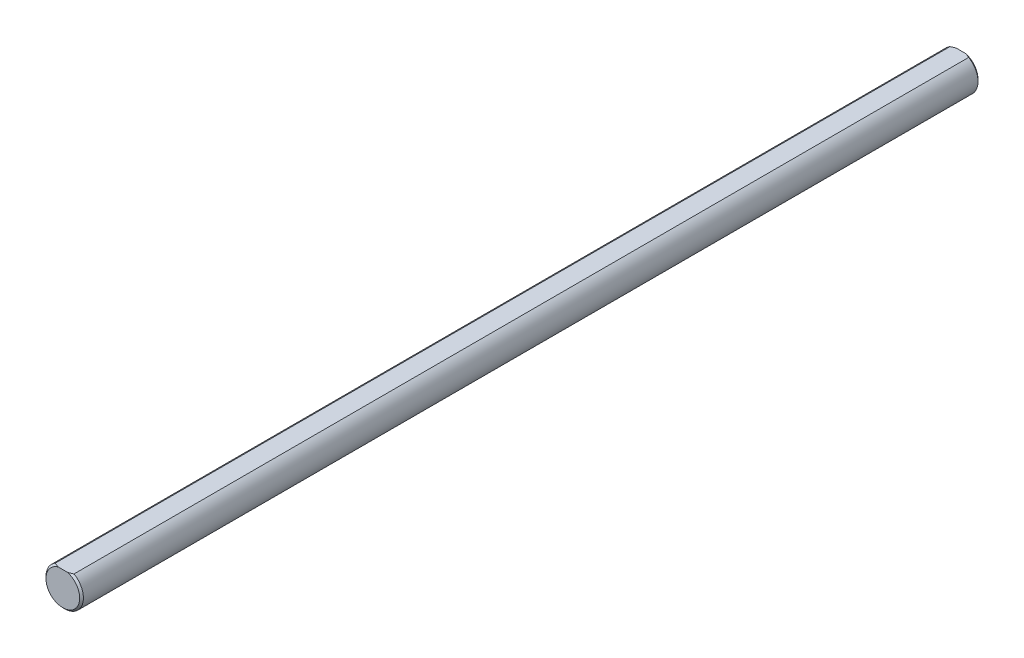
SolidWorks part; units mm, degrees
ref_plane "Front Plane" through (0, 0, 0) normal (0, 0, 1) x (1, 0, 0)
ref_plane "Top Plane" through (0, 0, 0) normal (0, 1, 0) x (1, 0, 0)
ref_plane "Right Plane" through (0, 0, 0) normal (1, 0, 0) x (0, 0, -1)
sketch "Sketch1" plane through (0, 0, 0) normal (0, 0, 1) x (1, 0, 0)
  circle A1 centre (0, 0) radius 3.175 construction
  dimension "Diameter" = 6.35
sketch "Sketch2" plane through (0, 0, 0) normal (1, 0, 0) x (0, 0, -1)
  line L0 (-76.2, 3.175) -> (76.2, 3.175) construction
  line L1 (0, 3.175) -> (0, -3.175) construction
  line L2 (0, 3.175) -> (0, -3.175) construction
  point P2 (0, 3.175)
  point P3 (63.5, 3.175)
  point P4 (-63.5, 3.175)
  dimension "Length" = 152.4
  dimension "D2" = 12.7
  dimension "D1" = 12.7
sketch "Sketch3" plane through (0, 0, 0) normal (0, 0, 1) x (1, 0, 0)
  circle A1 centre (0, 0) radius 3.175 construction
  circle A3 centre (0, 0) radius 3.175
extrude "Boss-Extrude2" add sketch "Sketch3" along normal up to vertex (76.2 mm away) and the other way up to vertex (76.2 mm away) up to point (0, 3.175, 76.2) other way up to point (0, 3.175, -76.2)
sketch "Sketch10" plane through (0, 0, 0) normal (0, 0, 1) x (1, 0, 0)
  line L0 (-1.5875, 2.7496) -> (1.5875, 2.7496)
  line L1 (0, 0) -> (0, 3.175) construction
  circle A0 centre (0, 0) radius 3.175 construction
  circle A1 centre (0, 0) radius 3.175 construction
  arc A2 (-1.5875, 2.7496) -> (1.5875, 2.7496) centre (0, 0) cw
extrude "Cut-Extrude5" cut sketch "Sketch10" against normal through all both and the other way through all
chamfer "Chamfer1" distance 0.3175 angle 45 4 edges at (0, -3.175, 76.2) (0, -3.175, -76.2) (0, 2.7496, -76.2) (0, 2.7496, 76.2)
equation "\"D1@Chamfer1\"= \"Diameter@Sketch1\" / 20"
equation "\"D1@Sketch2\"=\"Diameter@Sketch1\"*2"
equation "\"D2@Sketch2\"=\"D1@Sketch2\""
